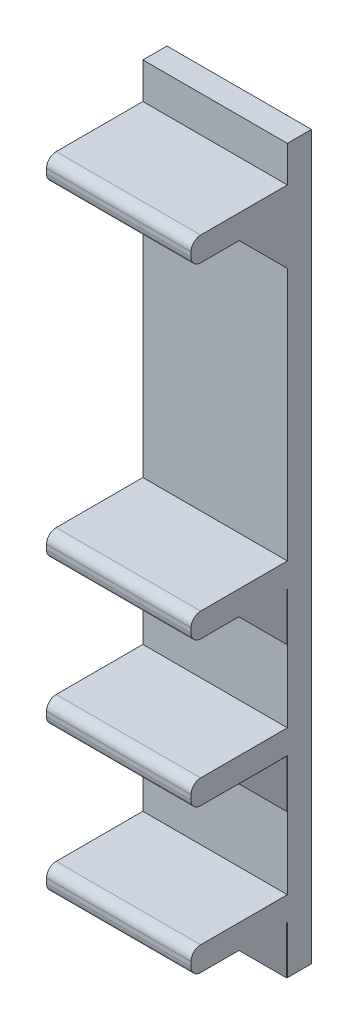
SolidWorks part; units mm, degrees
ref_plane "Front Plane" through (0, 0, 0) normal (0, 0, 1) x (1, 0, 0)
ref_plane "Top Plane" through (0, 0, 0) normal (0, 1, 0) x (1, 0, 0)
ref_plane "Right Plane" through (0, 0, 0) normal (1, 0, 0) x (0, 0, -1)
sketch "Sketch1" plane through (0, 0, 0) normal (0, 0, 1) x (1, 0, 0)
  line L1 (0, 0) -> (19.05, 0)
  line L2 (0, 0) -> (0, 95.25)
  line L3 (0, 95.25) -> (19.05, 95.25)
  line L4 (19.05, 0) -> (19.05, 95.25)
  dimension "D1" = 19.05
  dimension "D2" = 95.25
extrude "Boss-Extrude1" add sketch "Sketch1" against normal blind 3.175
sketch "Sketch2" plane through (0, 0, 0) normal (0, 0, 1) x (1, 0, 0)
  line L0 (0, 95.25) -> (0, 0) construction
  line L1 (0, 9.4742) -> (19.05, 9.4742)
  line L2 (0, 9.4742) -> (0, 6.2992)
  line L3 (0, 6.2992) -> (19.05, 6.2992)
  line L4 (19.05, 9.4742) -> (19.05, 6.2992)
  line L5 (19.05, 0) -> (19.05, 95.25) construction
  line L7 (0, 28.5242) -> (19.05, 28.5242)
  line L8 (0, 28.5242) -> (0, 25.3492)
  line L9 (0, 25.3492) -> (19.05, 25.3492)
  line L10 (19.05, 28.5242) -> (19.05, 25.3492)
  line L11 (0, 47.5742) -> (19.05, 47.5742)
  line L12 (0, 47.5742) -> (0, 44.3992)
  line L13 (0, 44.3992) -> (19.05, 44.3992)
  line L14 (19.05, 47.5742) -> (19.05, 44.3992)
  line L15 (0, 90.5002) -> (19.05, 90.5002)
  line L16 (0, 90.5002) -> (0, 87.3252)
  line L17 (0, 87.3252) -> (19.05, 87.3252)
  line L18 (19.05, 90.5002) -> (19.05, 87.3252)
  dimension "D1" = 3.175
  dimension "D2" = 3.175
  dimension "D3" = 3.175
  dimension "D4" = 3.175
  dimension "D5" = 19.05
  dimension "D6" = 19.05
  dimension "D7" = 9.4742
  dimension "D8" = 42.926
extrude "Boss-Extrude2" add sketch "Sketch2" along normal blind 12.7
sketch "Sketch3" plane through (19.05, 0, 0) normal (1, 0, 0) x (0, 0, -1)
  line L0 (-6.35, 87.3252) -> (0, 80.9752)
  line L1 (-12.7, 87.3252) -> (0, 87.3252) construction
  line L2 (0, 47.5742) -> (0, 87.3252) construction
  line L3 (0, 109.5502) -> (0, 87.3252)
  line L4 (0, 87.3252) -> (-6.35, 87.3252)
  line L5 (-6.4267, 44.424) -> (-0.0767, 38.074)
  line L6 (-0.0767, 38.074) -> (-0.0767, 44.424)
  line L7 (-0.0767, 44.424) -> (-6.4267, 44.424)
  line L8 (-6.3886, 25.3218) -> (-0.0386, 18.9718)
  line L9 (-0.0386, 18.9718) -> (-0.0386, 25.3218)
  line L10 (-0.0386, 25.3218) -> (-6.3886, 25.3218)
  line L11 (-6.4497, 6.365) -> (-0.0997, 0.015)
  line L12 (-0.0997, 0.015) -> (-0.0997, 6.365)
  line L13 (-0.0997, 6.365) -> (-6.4497, 6.365)
  line M8 (-12.7, 87.3252) -> (0, 87.3252)
  line M9 (0, 87.3252) -> (0, 47.5742)
  line M12 (-12.7, 44.3992) -> (0, 44.3992)
extrude "Boss-Extrude3" add sketch "Sketch3" against normal blind 19.05 contours L0 M8 M9 | L5 L6 M12 | L9 L10 L8 | L11 L12 L13
fillet "Fillet1" radius 1.27 8 edges at (9.525, 6.2992, 12.7) (9.525, 9.4742, 12.7) (9.525, 25.3492, 12.7) (9.525, 28.5242, 12.7) (9.525, 44.3992, 12.7) (9.525, 47.5742, 12.7) (9.525, 87.3252, 12.7) (9.525, 90.5002, 12.7)
